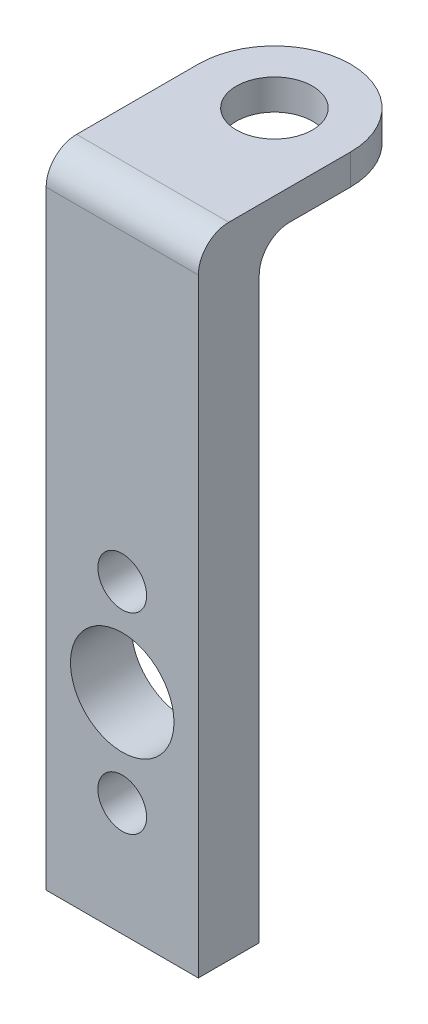
SolidWorks part; units mm, degrees
ref_plane "Front Plane" through (0, 0, 0) normal (0, 0, 1) x (1, 0, 0)
ref_plane "Top Plane" through (0, 0, 0) normal (0, 1, 0) x (1, 0, 0)
ref_plane "Right Plane" through (0, 0, 0) normal (1, 0, 0) x (0, 0, -1)
sketch "Sketch2" plane through (0, 0, 0) normal (0, 1, 0) x (1, 0, 0)
  line L4 (-6.35, 0) -> (-6.35, -12.7)
  line L5 (-6.35, -12.7) -> (6.35, -12.7)
  line L6 (6.35, 0) -> (6.35, -12.7)
  circle A0 centre (0, 0) radius 3.175
  arc A1 (-6.35, 0) -> (6.35, 0) centre (0, 0) cw
  dimension "D1" = 6.35
  dimension "D2" = 6.35
  dimension "D3" = 6.35
  dimension "D4" = 12.7
extrude "Boss-Extrude1" add sketch "Sketch2" along normal blind 2.54
sketch "Sketch4" plane through (0, 0, 0) normal (0, -1, 0) x (1, 0, 0)
  line L0 (6.35, 12.7) -> (6.35, 0) construction
  line L1 (-6.35, 12.7) -> (6.35, 12.7)
  line L2 (-6.35, 12.7) -> (-6.35, 7.62)
  line L3 (-6.35, 7.62) -> (6.35, 7.62)
  line L4 (6.35, 12.7) -> (6.35, 7.62)
  dimension "D1" = 5.08
extrude "Boss-Extrude2" add sketch "Sketch4" along normal blind 50.8
fillet "Fillet1" radius 2.54 1 edges at (0, 2.54, 12.7)
fillet "Fillet2" radius 2.54 1 edges
sketch "Sketch5" plane through (0, 0, 12.7) normal (0, 0, 1) x (1, 0, 0)
  line L0 (6.35, 0) -> (-6.35, 0) construction
  circle A0 centre (0, -33.3375) radius 4.318
  circle A1 centre (0, -25.3365) radius 2.032
  dimension "D2" = 8.636
  dimension "D3" = 4.064
  dimension "D1" = 33.3375
  dimension "D4" = 8.001
extrude "Cut-Extrude1" cut sketch "Sketch5" against normal through all contours A1 | A0
pattern_circular "CirPattern1" count 2 over 360 about axis through (0, -33.3375, 0) along (0, 0, 1) of "Cut-Extrude1"
